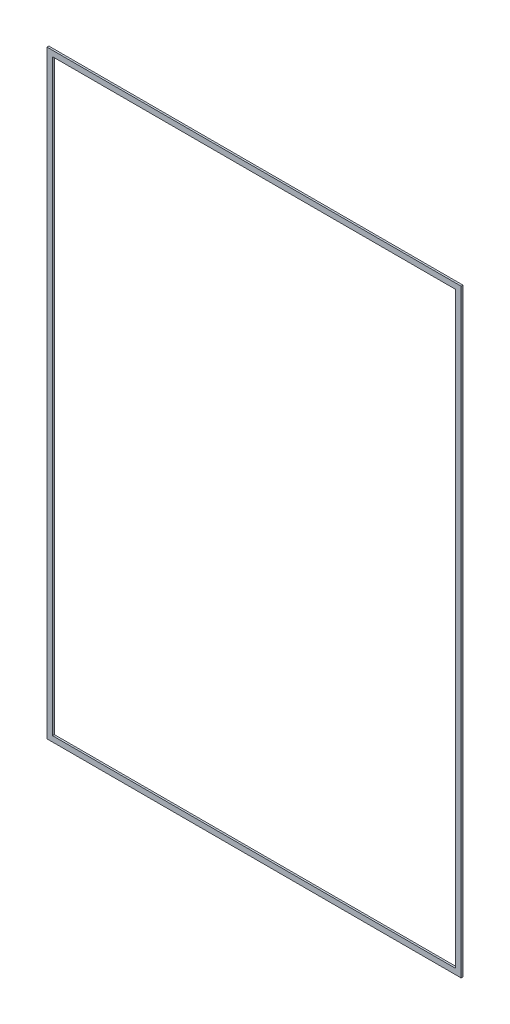
SolidWorks part; units mm, degrees
ref_plane "Front Plane" through (0, 0, 0) normal (0, 0, 1) x (1, 0, 0)
ref_plane "Top Plane" through (0, 0, 0) normal (0, 1, 0) x (1, 0, 0)
ref_plane "Right Plane" through (0, 0, 0) normal (1, 0, 0) x (0, 0, -1)
sketch "Sketch1" plane through (0, 0, 0) normal (0, 0, 1) x (1, 0, 0)
  line L1 (0, 0) -> (224, 0)
  line L2 (0, 0) -> (0, 324)
  line L3 (0, 324) -> (224, 324)
  line L4 (224, 0) -> (224, 324)
  line L5 (3, 3) -> (221, 3)
  line L6 (3, 3) -> (3, 321)
  line L7 (3, 321) -> (221, 321)
  line L8 (221, 3) -> (221, 321)
  dimension "D1" = 3
  dimension "D2" = 221
  dimension "D3" = 224
  dimension "D4" = 3
  dimension "D5" = 321
  dimension "D6" = 324
extrude "Profile" add sketch "Sketch1" along normal blind 1
equation "\"Profile_Depth\"= 1mm"
equation "\"D1@Profile\" = \"Profile_Depth\""
equation "\"Profile_Sketch_1\"= 3mm"
equation "\"D1@Sketch1\" = \"Profile_Sketch_1\""
equation "\"Profile_Sketch_2\"= 221mm"
equation "\"D2@Sketch1\" = \"Profile_Sketch_2\""
equation "\"Profile_Sketch_3\"= 224mm"
equation "\"D3@Sketch1\" = \"Profile_Sketch_3\""
equation "\"Profile_Sketch_4\"= 3mm"
equation "\"D4@Sketch1\" = \"Profile_Sketch_4\""
equation "\"Profile_Sketch_5\"= 321mm"
equation "\"D5@Sketch1\" = \"Profile_Sketch_5\""
equation "\"Profile_Sketch_6\"= 324mm"
equation "\"D6@Sketch1\" = \"Profile_Sketch_6\""
equation "\"EnvelopeWidth\"= 224mm"
equation "\"EnvelopeHeight\"= 324mm"
